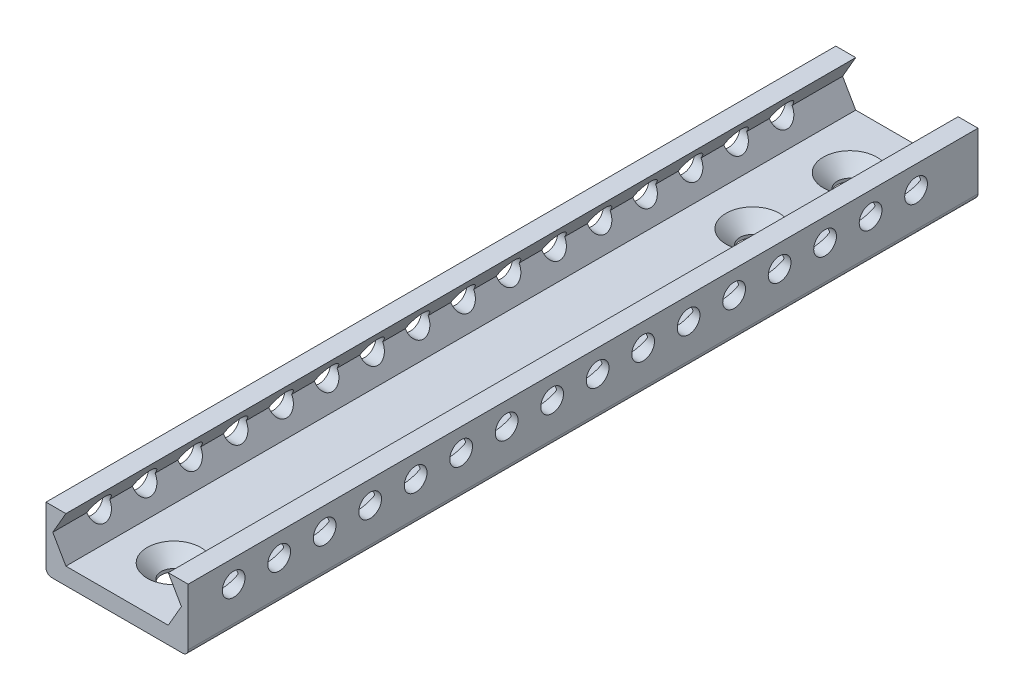
SolidWorks part; units mm, degrees
ref_plane "Front Plane" through (0, 0, 0) normal (0, 0, 1) x (1, 0, 0)
ref_plane "Top Plane" through (0, 0, 0) normal (0, 1, 0) x (1, 0, 0)
ref_plane "Right Plane" through (0, 0, 0) normal (1, 0, 0) x (0, 0, -1)
sketch "Sketch1" plane through (0, 0, 0) normal (0, 0, 1) x (1, 0, 0)
  line L0 (-9, 0) -> (9, 0)
  line L1 (-9, 0) -> (-11.3094, 4)
  line L2 (-11.3094, 4) -> (-9, 8)
  line L3 (-9, 8) -> (9, 8) construction
  line L4 (9, 8) -> (11.3094, 4)
  line L5 (11.3094, 4) -> (9, 0)
  line L6 (-9, 0) -> (-12.5, 0) construction
  line L8 (-12.5, 8) -> (-9, 8)
  line L9 (9, 8) -> (12.5, 8)
  line L10 (12.5, 8) -> (12.5, -3)
  line L11 (-12.5, 8) -> (-12.5, -3)
  line L12 (-12.5, -3) -> (12.5, -3)
  dimension "D1" = 18
  dimension "D2" = 120
  dimension "D3" = 120
  dimension "D4" = 120
  dimension "D5" = 120
  dimension "D6" = 8
  dimension "D7" = 3
  dimension "D8" = 3.5
extrude "Boss-Extrude1" add sketch "Sketch1" against normal blind 138.8861
sketch "Sketch2" plane through (0, 0, 0) normal (0, 1, 0) x (1, 0, 0)
  line L0 (9, 138.8861) -> (-9, 138.8861) construction
  line L1 (9, 0) -> (-9, 0) construction
  line L2 (0, 124.6082) -> (0, -49875.3918) construction
  circle A0 centre (0, 128.8861) radius 2
  circle A1 centre (0, 10) radius 2
  circle A2 centre (0, 111.7661) radius 2
  point P14 (0, 138.8861)
  dimension "D1" = 4
  dimension "D4" = 4
  dimension "D2" = 10
  dimension "D3" = 10
  dimension "D5" = 17.12
sketch "Sketch3" plane through (12.5, 0, 0) normal (1, 0, 0) x (0, 0, -1)
  line L0 (138.8861, 4) -> (0, 4) construction
  line L1 (0, -3) -> (0, 8) construction
  circle A0 centre (8, 4) radius 2
  dimension "D1" = 4
  dimension "D2" = 8
extrude "Cut-Extrude2" cut sketch "Sketch3" against normal blind 100
pattern_linear "LPattern1" count 16 spacing 8 along (0, 0, -1) of "Cut-Extrude2"
fillet "Fillet1" radius 1 2 edges at (12.5, -3, -69.4431) (-12.5, -3, -69.4431)
hole_wizard "CSK for M4 Flat Head Machine Screw1" positions "Sketch4" profile "Sketch5" countersink size "M4" standard "ANSI Metric" end condition through all
sketch "Sketch4" plane through (0, 0, 0) normal (0, 1, 0) x (1, 0, 0)
  point P0 (0, 10)
  point P3 (0, 128.8861)
  point P6 (0, 111.7661)
sketch "Sketch5" plane through (0, 0, -10) normal (1, 0, 0) x (0, 0, 1)
  line L0 (0, 0) -> (0, 3)
  line L1 (0, 3) -> (2.25, 3)
  line L2 (2.25, 3) -> (2.25, 2.45)
  line L3 (2.25, 2.45) -> (4.7, 0)
  line L5 (4.7, 0) -> (0, 0)
  line L6 (-2.25, 2.45) -> (-4.7, 0) construction
  line L11 (0, -6.35) -> (0, 107.95) construction
  dimension "Thru Hole Dia." = 4.5
  dimension "Thru Hole Depth" = 3
  dimension "Near C'Sink Dia." = 9.4
  dimension "Near C'Sink Angle" = 90
